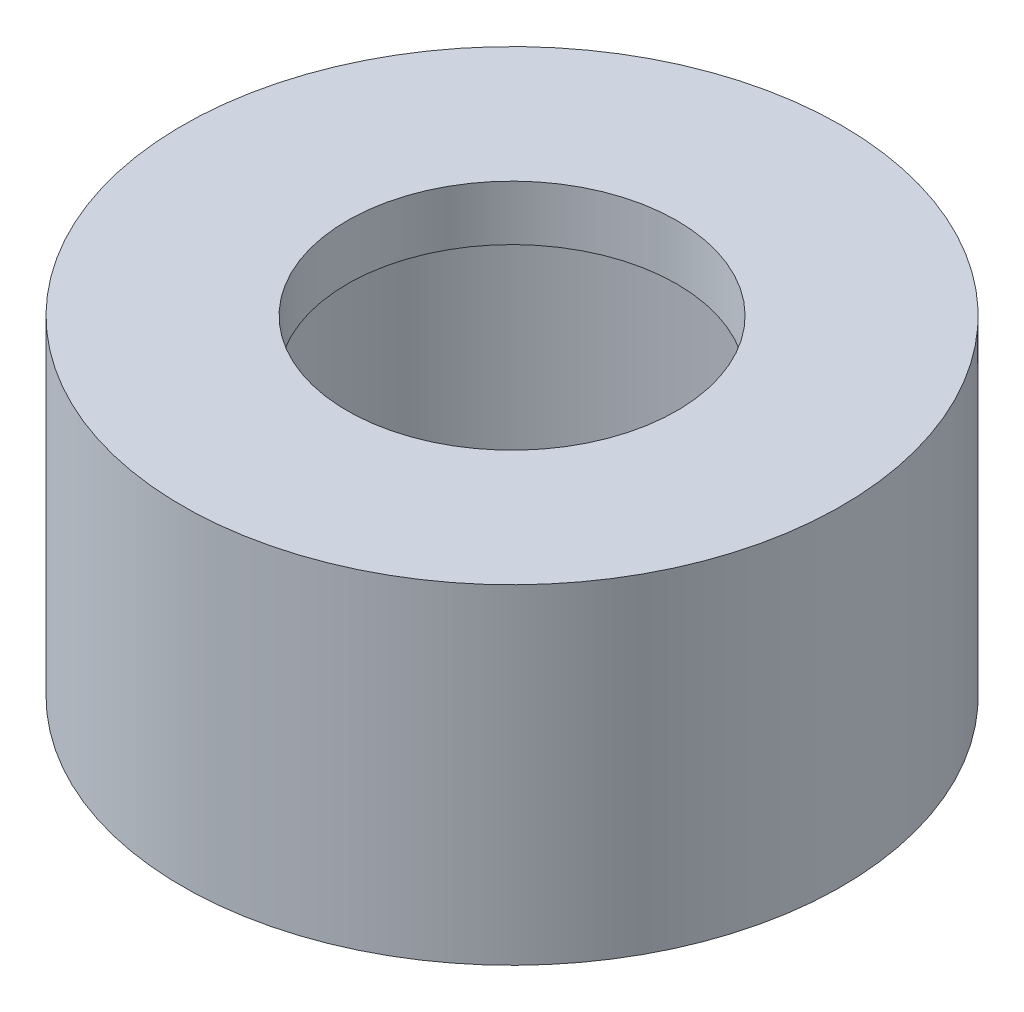
SolidWorks part; units mm, degrees
ref_plane "Front Plane" through (0, 0, 0) normal (0, 0, 1) x (1, 0, 0)
ref_plane "Top Plane" through (0, 0, 0) normal (0, 1, 0) x (1, 0, 0)
ref_plane "Right Plane" through (0, 0, 0) normal (1, 0, 0) x (0, 0, -1)
sketch "Sketch4" plane through (0, 0, 0) normal (0, 0, 1) x (1, 0, 0)
  line L0 (0, 0) -> (0, 33.1305) construction
sketch "Sketch3" plane through (0, 0, 0) normal (0, 0, 1) x (1, 0, 0)
  line L1 (-25, 0) -> (-30, 0)
  line L2 (-25, 0) -> (-25, 25)
  line L4 (-30, 0) -> (-30, 30)
  line L5 (-25, 25) -> (-15, 25)
  line L7 (-30, 30) -> (-15, 30)
  line L8 (-15, 25) -> (-15, 30)
  point P1 (0, 0)
  point P7 (-25.5215, 33.0675)
  point P8 (-25.5215, 44.1104)
  point P10 (-20, 28.5907)
  point P11 (0, 0)
  dimension "D1" = 30
  dimension "D2" = 5
  dimension "D3" = 30
  dimension "D4" = 10
revolve "Revolve1" add sketch "Sketch3" angle 360 about L0
